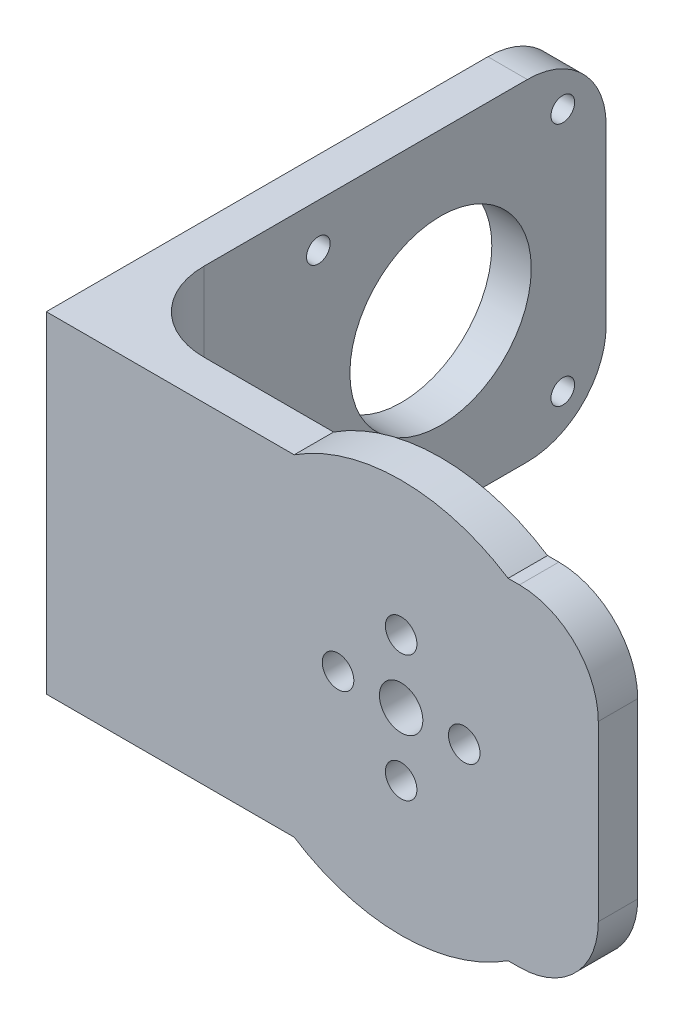
SolidWorks part; units mm, degrees
ref_plane "前视基准面" through (0, 0, 0) normal (0, 0, 1) x (1, 0, 0)
ref_plane "上视基准面" through (0, 0, 0) normal (0, 1, 0) x (1, 0, 0)
ref_plane "右视基准面" through (0, 0, 0) normal (1, 0, 0) x (0, 0, -1)
sketch "草图1" plane through (0, 0, 0) normal (0, 0, 1) x (1, 0, 0)
  line L1 (25, -21) -> (-25, -21)
  line L2 (25, -21) -> (25, 21)
  line L3 (25, 21) -> (-25, 21)
  line L4 (-25, -21) -> (-25, 21)
  line L5 (0, 21) -> (0, -21) construction
  line L6 (25, 0) -> (-25, 0) construction
  line L7 (-25, 21) -> (-40, 21)
  line L8 (-25, 21) -> (-25, -21)
  line L9 (-25, -21) -> (-40, -21)
  line L10 (-40, 21) -> (-40, -21)
  circle A0 centre (0, 0) radius 25
  point P0 (0, 0)
  dimension "D3" = 50
  dimension "D1" = 42
  dimension "D2" = 65
  dimension "D4" = 50
extrude "凸台-拉伸1" add sketch "草图1" along normal blind 5 contours L3 A0 L1 | L3 A0 | A0 L3 L4 L1 | A0 L1 L2 L3 | L1 A0 | L8 L7 L10 L9
sketch "草图2" plane through (0, 0, 5) normal (0, 0, 1) x (1, 0, 0)
  line L0 (-13.5647, 21) -> (-40, 21) construction
  line L1 (-45, 21) -> (-40, 21)
  line L2 (-45, 21) -> (-45, -21)
  line L3 (-45, -21) -> (-40, -21)
  line L4 (-40, 21) -> (-40, -21)
  line L7 (-40, 21) -> (-40, -21) construction
  line L9 (-13.5647, -21) -> (-40, -21) construction
  dimension "D1" = 5
extrude "凸台-拉伸2" add sketch "草图2" against normal blind 66
sketch "草图3" plane through (-45, 0, 0) normal (-1, 0, 0) x (0, 0, 1)
  line L0 (-61, 21) -> (5, 21) construction
  line L1 (-61, -21) -> (-19, -21)
  line L2 (-61, -21) -> (-61, 21)
  line L3 (-61, 21) -> (-19, 21)
  line L4 (-19, -21) -> (-19, 21)
  line L5 (-40, 21) -> (-40, -21) construction
  line L6 (-61, 0) -> (-19, 0) construction
  line L7 (-61, 21) -> (-61, -21) construction
  line L9 (-24.5, -15.5) -> (-55.5, -15.5) construction
  line L10 (-24.5, -15.5) -> (-24.5, 15.5) construction
  line L11 (-24.5, 15.5) -> (-55.5, 15.5) construction
  line L12 (-55.5, -15.5) -> (-55.5, 15.5) construction
  line L13 (-40, 15.5) -> (-40, -15.5) construction
  line L14 (-24.5, 0) -> (-55.5, 0) construction
  circle A0 centre (-24.5, 15.5) radius 1.5
  circle A1 centre (-24.5, 74.5) radius 1.5
  circle A2 centre (34.5, 74.5) radius 1.5
  circle A3 centre (34.5, 15.5) radius 1.5
  circle A4 centre (-40, 0) radius 11.5
  circle A5 centre (-24.5, -15.5) radius 1.5
  circle A6 centre (-55.5, -15.5) radius 1.5
  circle A7 centre (-55.5, 15.5) radius 1.5
  point P0 (-40, 0)
  point P11 (-40, 0)
  point P28 (5, 45)
  point P37 (-40, 0)
  dimension "D4" = 3
  dimension "D6" = 23
  dimension "D1" = 42
  dimension "D2" = 31
  dimension "D3" = 31
  dimension "D5" = 4
  dimension "D7" = 4
extrude "切除-拉伸1" cut sketch "草图3" against normal blind 5 contours A4 | A7 | A6 | A0 | A5 | A2
sketch "草图5" plane through (0, 0, 0) normal (0, 0, -1) x (-1, 0, 0)
  circle A0 centre (0, 0) radius 8 construction
  circle A1 centre (0, 8) radius 2
  circle A2 centre (8, 0) radius 2
  circle A3 centre (0, -8) radius 2
  circle A4 centre (-8, 0) radius 2
  circle A5 centre (0, 0) radius 2.75
  point P14 (0, 0)
  dimension "D1" = 16
  dimension "D2" = 4
  dimension "D4" = 5.5
  dimension "D3" = 4
extrude "切除-拉伸2" cut sketch "草图5" against normal through all
fillet "圆角1" radius 10 1 edges at (-40, 0, 0)
fillet "圆角2" radius 10 4 edges at (25, 21, 2.5) (25, -21, 2.5) (-42.5, -21, -61) (-42.5, 21, -61)
sketch "草图6" plane through (0, 0, 5) normal (0, 0, 1) x (1, 0, 0)
  circle A0 centre (0, 0) radius 12.5
  circle A1 centre (0, 0) radius 17.5
  dimension "D1" = 25
  dimension "D2" = 35
